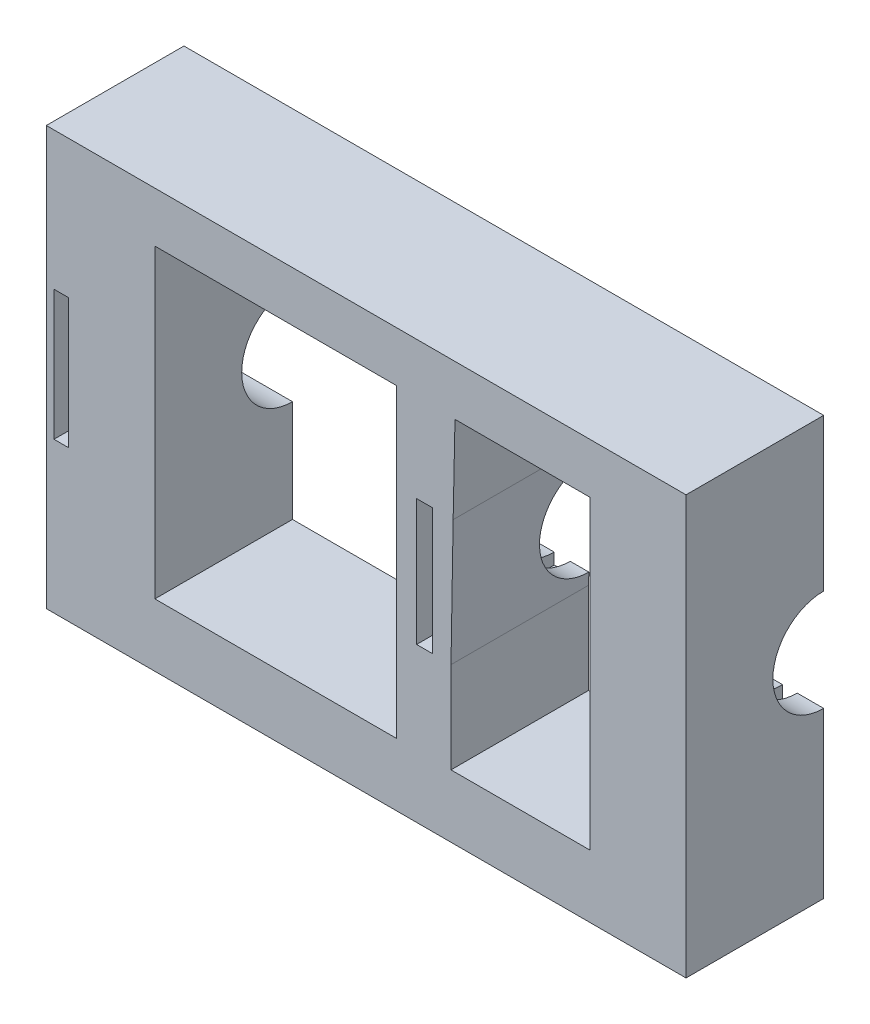
SolidWorks part; units mm, degrees
ref_plane "Front Plane" through (0, 0, 0) normal (0, 0, 1) x (1, 0, 0)
ref_plane "Top Plane" through (0, 0, 0) normal (0, 1, 0) x (1, 0, 0)
ref_plane "Right Plane" through (0, 0, 0) normal (1, 0, 0) x (0, 0, -1)
sketch "Sketch1" plane through (0, 0, 0) normal (0, 1, 0) x (1, 0, 0)
  line L3 (3.9498, 3.2101) -> (3.9498, 17.1069)
  line L4 (5.423, 3.2101) -> (5.423, 17.1069)
  line L5 (3.9498, 17.1069) -> (0, 17.1069)
  line L6 (0, 17.1069) -> (0, 0)
  line L7 (3.9498, 3.2101) -> (5.423, 3.2101)
  line L8 (10.9894, 3.2101) -> (10.9894, 0)
  line L9 (0, 0) -> (0, -3.1783)
  line L10 (0, -3.1783) -> (66.04, -3.1783)
  line L11 (5.423, 17.1069) -> (10.9894, 17.1069)
  line L12 (10.9894, 17.1069) -> (10.9894, 3.2101)
  line L13 (10.9894, 0) -> (55.0506, 0)
  line L15 (55.0506, 17.1069) -> (55.0506, 3.2101)
  line L16 (60.617, 17.1069) -> (55.0506, 17.1069)
  line L17 (66.04, 0) -> (66.04, -3.1783)
  line L18 (55.0506, 3.2101) -> (55.0506, 0)
  line L19 (62.0902, 3.2101) -> (60.617, 3.2101)
  line L20 (66.04, 17.1069) -> (66.04, 0)
  line L21 (62.0902, 17.1069) -> (66.04, 17.1069)
  line L22 (60.617, 3.2101) -> (60.617, 17.1069)
  line L23 (62.0902, 3.2101) -> (62.0902, 17.1069)
extrude "Boss-Extrude1" add sketch "Sketch1" along normal blind 13.1572
sketch "Sketch2" plane through (0, 13.1572, 0) normal (0, 1, 0) x (1, 0, 0)
  line L0 (10.9894, 17.1069) -> (0, 17.1069)
  line L1 (0, 17.1069) -> (0, -3.1783)
  line L2 (0, -3.1783) -> (66.04, -3.1783)
  line L3 (0, -3.1783) -> (66.04, -3.1783) construction
  line L4 (66.04, -3.1783) -> (66.04, 17.1069)
  line L5 (66.04, 17.1069) -> (55.0506, 17.1069)
  line L6 (55.0506, 17.1069) -> (55.0506, -0.2263)
  line L7 (55.0506, -0.2263) -> (10.9894, 0)
  line L8 (10.9894, 0) -> (10.9894, 17.1069)
extrude "Boss-Extrude2" add sketch "Sketch2" along normal blind 8.89
sketch "Sketch3" plane through (0, 22.0472, 0) normal (0, 1, 0) x (1, 0, 0)
  line L0 (0, -3.1783) -> (66.04, -3.1783)
  line L1 (0, -3.1783) -> (66.04, -3.1783) construction
  line L2 (66.04, -3.1783) -> (66.04, 17.1069)
  line L3 (66.04, 17.1069) -> (0, 17.1069)
  line L4 (0, 17.1069) -> (0, -3.1783)
  point P9 (66.04, -3.1783)
extrude "Boss-Extrude3" add sketch "Sketch3" along normal blind 5.08
sketch "Sketch4" plane through (0, 0, 0) normal (0, -1, 0) x (1, 0, 0)
  line L0 (66.04, -17.1069) -> (55.0506, -17.1069)
  line L1 (55.0506, -17.1069) -> (55.0506, 0)
  line L2 (55.0506, 0) -> (10.9894, 0)
  line L3 (10.9894, 0) -> (10.9894, -17.1069)
  line L4 (10.9894, -17.1069) -> (0, -17.1069)
  line L5 (0, -17.1069) -> (0, 3.1783)
  line L6 (0, 3.1783) -> (66.04, 3.1783)
  line L7 (66.04, 3.1783) -> (66.04, -17.1069)
extrude "Boss-Extrude4" add sketch "Sketch4" along normal blind 8.89
sketch "Sketch6" plane through (55.0506, 0, 0) normal (-1, 0, 0) x (0, 0, 1)
  line L0 (-17.1069, 22.0472) -> (-17.1069, -8.89) construction
  circle A0 centre (-17.1069, 6.5786) radius 5.1435
extrude "Cut-Extrude1" cut sketch "Sketch6" against normal through all both and the other way through all
sketch "Sketch7" plane through (0, -8.89, 0) normal (0, -1, 0) x (1, 0, 0)
  line L1 (66.04, -17.1069) -> (0, -17.1069)
  line L2 (66.04, -17.1069) -> (66.04, 3.1783)
  line L3 (66.04, 3.1783) -> (0, 3.1783)
  line L4 (0, -17.1069) -> (0, 3.1783)
extrude "Boss-Extrude5" add sketch "Sketch7" along normal blind 25.4
sketch "Sketch9" plane through (0, 0, -17.1069) normal (0, 0, -1) x (-1, 0, 0)
  line L1 (-39.1063, 0.3654) -> (-39.1063, 13.1572)
  line L2 (-39.1063, 13.1572) -> (-37.4909, 13.1572)
  line L3 (-37.4909, 13.1572) -> (-37.4909, 0.3654)
  line L4 (-37.4909, 0.3654) -> (-39.1063, 0.3654)
  line L6 (-41.1891, 13.1572) -> (-40.9712, 0.3337)
  line L7 (-40.9712, 0.3337) -> (-40.9712, -8.89)
  line L8 (-10.9894, -8.89) -> (-55.0506, -8.89) construction
  line L9 (-40.9712, -8.89) -> (-37.4909, -8.89)
  line L10 (-37.4909, -8.89) -> (-35.4589, -8.89)
  line L11 (-35.4589, -8.89) -> (-35.4589, 13.1572)
  line L13 (-35.4589, -8.89) -> (-35.4589, 22.0472)
  line L14 (-55.0506, 22.0472) -> (-10.9894, 22.0472) construction
  line L15 (-35.4589, 22.0472) -> (-41.3759, 22.0472)
  line L16 (-41.3759, 22.0472) -> (-41.1891, 13.1572)
  line M28 (-10.9894, -8.89) -> (-55.0506, -8.89)
extrude "Boss-Extrude6" add sketch "Sketch9" against normal blind 19.05 contours L15 L16 L6 L7 L11 L13 L3 L4 L1 L2 M28
sketch "Sketch10" plane through (35.4589, 0, 0) normal (-1, 0, 0) x (0, 0, 1)
  line L0 (-17.1069, -8.89) -> (-17.1069, 22.0472) construction
  circle A0 centre (-17.1069, 6.5786) radius 5.08
extrude "Cut-Extrude2" cut sketch "Sketch10" against normal blind 15.24
sketch "Sketch12" plane through (66.04, 0, 0) normal (1, 0, 0) x (0, 0, -1)
  line L0 (17.1069, 27.1272) -> (17.1069, 11.7221)
  line L1 (17.1069, 27.1272) -> (-3.5261, 27.1272)
  line L2 (-3.5261, 27.1272) -> (-3.1783, -34.29)
  line L3 (-3.1783, 27.1272) -> (-3.1783, -34.29) construction
  line L4 (17.1069, -34.29) -> (-3.1783, -34.29) construction
  line L5 (-3.1783, -34.29) -> (17.1069, -34.29)
  line L6 (17.1069, -34.29) -> (17.1069, 1.4351)
  line L7 (17.1069, 11.7221) -> (17.1069, 1.4351)
extrude "Cut-Extrude3" cut sketch "Sketch12" against normal blind 1.27
sketch "Sketch14" plane through (0, 0, -17.1069) normal (0, 0, -1) x (-1, 0, 0)
  line L1 (-5.423, 13.1572) -> (-3.9498, 13.1572)
  line L2 (-5.423, 13.1572) -> (-5.423, 0)
  line L3 (-5.423, 0) -> (-3.9498, 0)
  line L4 (-3.9498, 13.1572) -> (-3.9498, 0)
  line L5 (-0.7748, 13.1572) -> (-0.7748, 0)
  line L6 (-0.7748, 0) -> (-2.248, 0)
  line L7 (-2.248, 0) -> (-2.248, 13.1572)
  line L8 (-2.248, 13.1572) -> (-0.7748, 13.1572)
extrude "Cut-Extrude4" cut sketch "Sketch14" against normal blind 15.24
sketch "Sketch15" plane through (0, -34.29, 0) normal (0, -1, 0) x (1, 0, 0)
  line L1 (64.77, 3.1783) -> (0, 3.1783)
  line L2 (64.77, 3.1783) -> (64.77, -17.1069)
  line L3 (64.77, -17.1069) -> (0, -17.1069)
  line L4 (0, 3.1783) -> (0, -17.1069)
extrude "Cut-Extrude5" cut sketch "Sketch15" against normal blind 19.05
sketch "Sketch16" plane through (5.423, 0, 0) normal (-1, 0, 0) x (0, 0, 1)
  line L0 (-17.1069, 13.1572) -> (6.0758, 13.1572)
  line L1 (6.0758, 13.1572) -> (6.0758, 0)
  line L2 (6.0758, 0) -> (-17.1069, 0)
  line L3 (-17.1069, 0) -> (-17.1069, 1.4351)
  line L5 (-17.1069, 11.7221) -> (-17.1069, 13.1572)
  arc A0 (-17.1069, 1.4351) -> (-17.1069, 11.7221) centre (-17.1069, 6.5786) ccw construction
  arc A1 (-17.1069, 1.4351) -> (-17.1069, 11.7221) centre (-17.1069, 6.5786) ccw
extrude "Boss-Extrude7" add sketch "Sketch16" along normal blind 1.4986
sketch "Sketch17" plane through (0, 0, 3.1783) normal (0, 0, 1) x (1, 0, 0)
  line L1 (0, 27.1272) -> (64.77, 27.1272)
  line L2 (0, 27.1272) -> (0, -15.24)
  line L3 (0, -15.24) -> (64.77, -15.24)
  line L4 (64.77, 27.1272) -> (64.77, -15.24)
extrude "Cut-Extrude7" cut sketch "Sketch17" against normal blind 6.35
